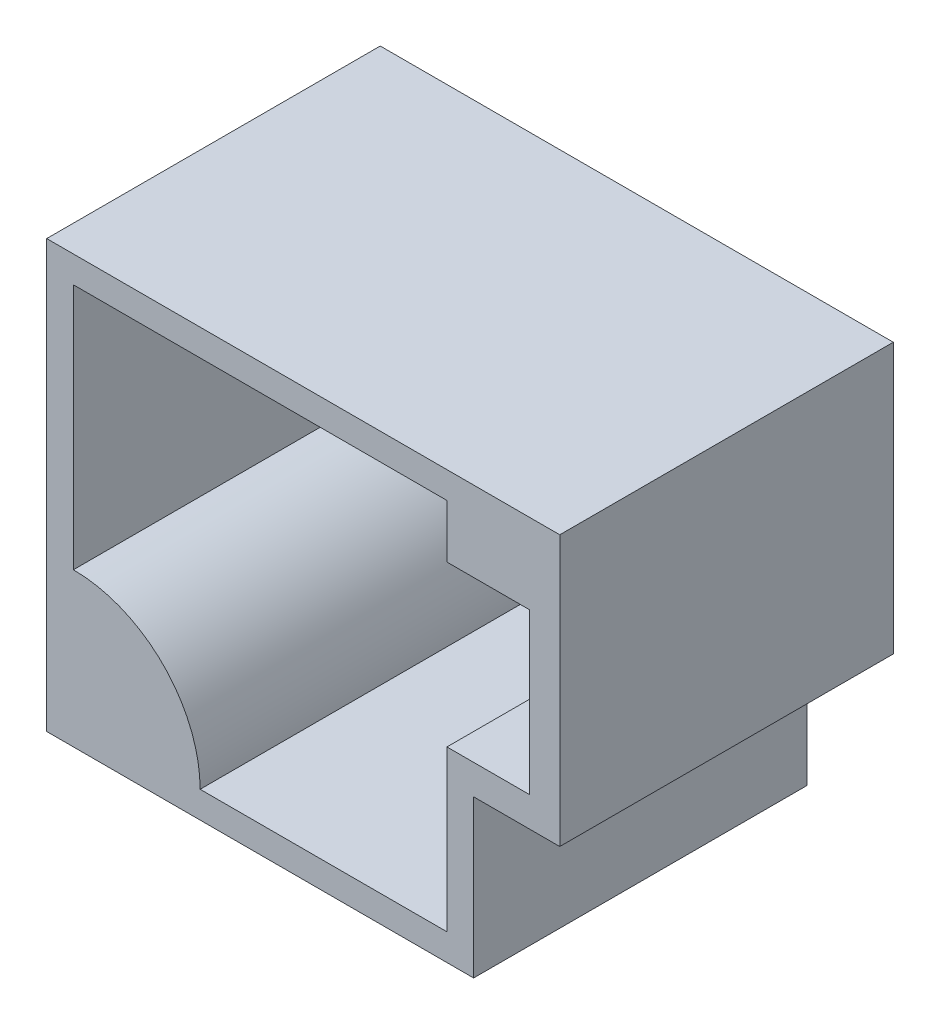
SolidWorks part; units mm, degrees
ref_plane "前视基准面" through (0, 0, 0) normal (0, 0, 1) x (1, 0, 0)
ref_plane "上视基准面" through (0, 0, 0) normal (0, 1, 0) x (1, 0, 0)
ref_plane "右视基准面" through (0, 0, 0) normal (1, 0, 0) x (0, 0, -1)
sketch "草图1" plane through (0, 0, 0) normal (0, 0, 1) x (1, 0, 0)
  line L1 (-140, 140) -> (140, 140)
  line L2 (-140, 140) -> (-140, -45)
  line L3 (-45, -140) -> (140, -140)
  line L4 (140, 140) -> (140, 100)
  line L5 (-140, 140) -> (140, -140) construction
  line L6 (-140, -140) -> (140, 140) construction
  line L10 (-160, -160) -> (160, -160)
  line L11 (160, -160) -> (160, -42.3687)
  line L12 (160, -42.3687) -> (224.5721, -42.3687)
  line L13 (224.5721, -42.3687) -> (224.5721, 160)
  line L14 (224.5721, 160) -> (-160, 160)
  line L15 (-160, 160) -> (-160, -160)
  line L16 (140, 100) -> (202, 100)
  line L17 (202, 100) -> (202, -20)
  line L18 (202, -20) -> (140, -20)
  line L19 (140, -20) -> (140, -140)
  arc A0 (-140, -45) -> (-45, -140) centre (-140, -140) cw
  point P0 (0, 0)
  dimension "D7" = 95
  dimension "D1" = 280
  dimension "D2" = 280
  dimension "D3" = 20
  dimension "D4" = 20
  dimension "D5" = 20
  dimension "D6" = 20
  dimension "D8" = 120
  dimension "D9" = 40
  dimension "D10" = 62
extrude "凸台-拉伸1" add sketch "草图1" along normal blind 250
sketch "草图2" plane through (0, 0, 0) normal (0, 0, -1) x (-1, 0, 0)
  line L1 (-202, 100) -> (-140, 100)
  line L2 (-202, 100) -> (-202, -20)
  line L3 (-202, -20) -> (-140, -20)
  line L4 (-140, 100) -> (-140, -20)
extrude "凸台-拉伸2" add sketch "草图2" against normal blind 60
